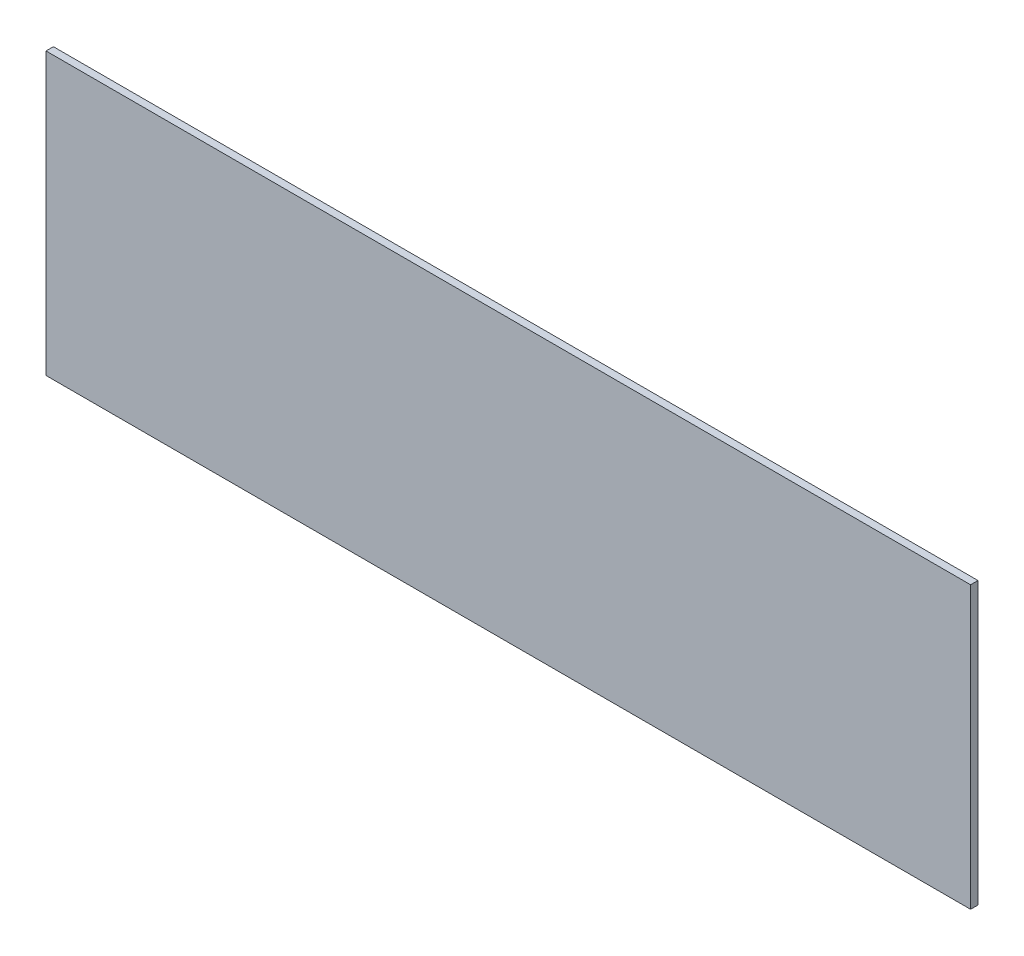
SolidWorks part; units mm, degrees
ref_plane "Front Plane" through (0, 0, 0) normal (0, 0, 1) x (1, 0, 0)
ref_plane "Top Plane" through (0, 0, 0) normal (0, 1, 0) x (1, 0, 0)
ref_plane "Right Plane" through (0, 0, 0) normal (1, 0, 0) x (0, 0, -1)
sketch "Sketch1" plane through (0, 0, 0) normal (0, 0, 1) x (1, 0, 0)
  line L1 (0, 0) -> (125, 0)
  line L2 (0, 0) -> (0, 38)
  line L3 (0, 38) -> (125, 38)
  line L4 (125, 0) -> (125, 38)
  dimension "D1" = 125
  dimension "D2" = 38
extrude "Profile" add sketch "Sketch1" along normal blind 1
equation "\"Profile_Depth\"= 1mm"
equation "\"D1@Profile\" = \"Profile_Depth\""
equation "\"Profile_Sketch_1\"= 125mm"
equation "\"D1@Sketch1\" = \"Profile_Sketch_1\""
equation "\"Profile_Sketch_2\"= 38mm"
equation "\"D2@Sketch1\" = \"Profile_Sketch_2\""
equation "\"EnvelopeWidth\"= 125mm"
equation "\"EnvelopeHeight\"= 38mm"
